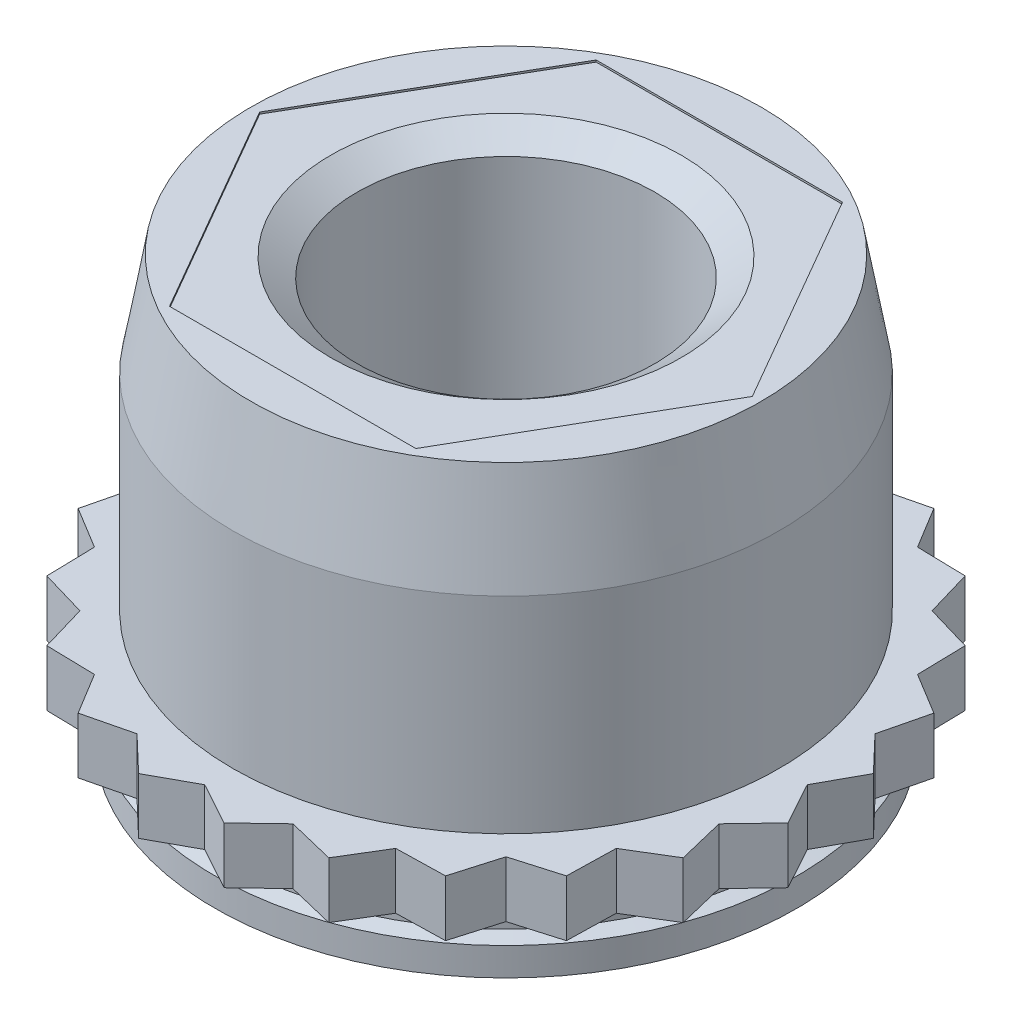
SolidWorks part; units mm, degrees
revolve "Body" add sketch "BodySke"
sketch "BodySke" plane through (0, 0, 0) normal (0, 0, 1) x (1, 0, 0)
  line L0 (3.7522, -1.0901) -> (3.7522, -0.762)
  line L1 (3.7084, 2.794) -> (3.4621, 4.191)
  line L2 (4.445, 0) -> (3.7084, 0)
  line L3 (2.0193, 4.191) -> (2.0193, -1.524)
  line L4 (2.0193, -1.524) -> (3.9497, -1.524)
  line L5 (3.9497, -1.524) -> (3.9497, -1.143)
  line L6 (3.9497, -1.143) -> (3.7522, -1.0901)
  line L7 (1.016, 0.7925) -> (3.7084, 0.7925) construction
  line L8 (3.7084, 0) -> (3.7084, 2.794)
  line L9 (0, 0) -> (0, 15.24) construction
  line L11 (3.4621, 4.191) -> (2.0193, 4.191)
  line L15 (3.7522, -0.762) -> (4.445, -0.762)
  line L16 (4.445, -0.762) -> (4.445, 0)
  dimension "Clinch_dia" = 8.89
  dimension "C_dia" = 7.8994
  dimension "Thread_min" = 4.0386
  dimension "Advance" = 0.7925
  dimension "D_dia" = 7.4168
  dimension "Height" = 4.191
  dimension "A_ht" = 1.524
  dimension "Clinching_ht" = 0.762
  dimension "Groove_dia" = 7.5044
  dimension "Chamfer_ht" = 1.397
  dimension "D1" = 10
  dimension "D2" = 75
  dimension "C_len" = 0.381
cosmetic thread "ThreadCosmetic" [suppressed]
revolve "EndChamfer" cut sketch "EndChamferSke" angle 360 about L0
sketch "EndChamferSke" plane through (0, 0, 0) normal (0, 0, 1) x (1, 0, 0)
  line L0 (0, -2.54) -> (0, 7.62) construction
  line L1 (0, 0) -> (0, 15.24) construction
  line L2 (2.413, -1.778) -> (2.413, -1.5215)
  line L3 (2.413, -1.5215) -> (2.0193, -1.2459)
  line L4 (2.0193, -1.2459) -> (2.0193, -1.778)
  line L5 (2.0193, -1.778) -> (2.413, -1.778)
  line L6 (2.413, 4.1885) -> (2.413, 4.445)
  line L7 (2.413, 4.445) -> (2.0193, 4.445)
  line L8 (2.0193, 4.445) -> (2.0193, 3.9129)
  line L9 (2.0193, 3.9129) -> (2.413, 4.1885)
  line L10 (3.4621, 4.191) -> (-3.4621, 4.191) construction
  line L11 (-3.9497, -1.524) -> (3.9497, -1.524) construction
  line L12 (2.0193, 4.191) -> (-2.0193, 4.191) construction
  dimension "Thread_nominal" = 4.826
  dimension "Thread_min" = 4.0386
  dimension "D1" = 0.254
  dimension "D2" = 34.99
  dimension "D3" = 0.254
ref_plane "Plane1" through (0, 0, 0) normal (0, 0, 1) x (1, 0, 0)
ref_plane "Plane2" through (0, 0, 0) normal (0, 1, 0) x (1, 0, 0)
ref_plane "Plane3" through (0, 0, 0) normal (1, 0, 0) x (0, 0, -1)
ref_plane "Plane4" through (0, -0.5486, 0) normal (0, 1, 0) x (-1, 0, 0)
sketch "ThdSchSke" plane through (0, 0, 0) normal (0, 0, 1) x (1, 0, 0)
  line L0 (0, -5.08) -> (0, 7.62) construction
  line L1 (0, 0) -> (0, 15.24) construction
  line L2 (0, -1.5215) -> (2.413, -1.5215) construction
  line L4 (2.413, -1.5215) -> (2.0193, -1.2458)
  line L6 (2.413, -1.5215) -> (2.0193, -1.7971)
  line L7 (2.0193, -1.2458) -> (2.0193, -1.7971)
  line L8 (2.413, -1.5215) -> (-2.413, -1.5215) construction
  dimension "Thread_nominal" = 4.826
  dimension "Thread_min" = 4.0386
revolve "ThreadSchematic" [suppressed] cut sketch "ThdSchSke" angle 360 about L0
pattern_linear "ThdSchPat" [suppressed]
sketch "CliRinCutSke" plane through (0, -0.762, 0) normal (0, -1, 0) x (1, 0, 0)
  line L0 (0.5802, 4.407) -> (0, 4.0894)
  line L1 (0, 4.0894) -> (-0.5802, 4.407)
  line L2 (0, 0) -> (0, 5.842) construction
  arc A1 (0.5802, 4.407) -> (-0.5802, 4.407) centre (0, 0) ccw
  circle A2 centre (0, 0) radius 4.0894 construction
  dimension "Angle" = 15
  dimension "Clinch_dia" = 8.89
  dimension "Clinch_minor" = 8.1788
extrude "ClinchCut" cut sketch "CliRinCutSke" against normal blind 0.762
pattern_circular "ClinchCutPat" count 24 every 15 about axis through (0, 0, 0) along (0, 1, 0) of "ClinchCut"
sketch "HexCutSke" plane through (0, 4.191, 0) normal (0, 1, 0) x (-1, 0, 0)
  line L0 (-1.6718, 2.8956) -> (1.6718, 2.8956)
  line L1 (1.6718, 2.8956) -> (3.3436, 0)
  line L2 (3.3436, 0) -> (1.6718, -2.8956)
  line L3 (1.6718, -2.8956) -> (-1.6718, -2.8956)
  line L4 (-1.6718, -2.8956) -> (-3.3436, 0)
  line L5 (-3.3436, 0) -> (-1.6718, 2.8956)
  circle A0 centre (0, 0) radius 3.3436 construction
  circle A1 centre (0, 0) radius 2.8956 construction
  dimension "Width_across_flats" = 5.7912
extrude "HexCut" cut sketch "HexCutSke" against normal blind 0.0254
equation "' \"A_ht@BodySke\" = 0.06"
equation "' \"C_dia@BodySke\" = 0.311"
equation "' \"D_dia@BodySke\" = 0.292"
equation "' \"Clinch_dia@BodySke\" = 0.35"
equation "' \"Height@BodySke\" = 0.165"
equation "' \"Advance@BodySke\" = 0.0312"
equation "' \"Thread_min@BodySke\" = 0.159"
equation "' \"Thread_nominal@ThreadCosmetic\" = 0.19"
equation "\"Width_across_flats@HexCutSke\" = \"Thread_nominal@ThreadCosmetic\" * 1.2"
equation "\"Count@ClinchCutPat\" = 24"
equation "\"Angle@ClinchCutPat\" = 360 / \"Count@ClinchCutPat\""
equation "\"Angle@CliRinCutSke\" = 360 / \"Count@ClinchCutPat\""
equation "\"Clinch_dia@CliRinCutSke\" = \"Clinch_dia@BodySke\""
equation "\"Clinch_minor@CliRinCutSke\" = \"Clinch_dia@BodySke\" * 0.92"
equation "\"C_len@BodySke\" = \"A_ht@BodySke\" * 0.25"
equation "\"Groove_dia@BodySke\" = \"C_dia@BodySke\" * 0.95"
equation "\"Clinching_ht@BodySke\" = \"A_ht@BodySke\" * 0.5"
equation "\"Depth@ClinchCut\" =  \"A_ht@BodySke\" * 0.5"
equation "\"Chamfer_ht@BodySke\" = \"Height@BodySke\" / 3"
equation "\"Thread_nominal@EndChamferSke\" = \"Thread_nominal@ThreadCosmetic\""
equation "\"Thread_min@EndChamferSke\" = \"Thread_min@BodySke\""
equation "\"D2@EndChamferSke\" = \"Vee_angle@ThdSchSke\" / 2 - 0.01"
equation "\"Thread_nominal@ThdSchSke\" = \"Thread_nominal@ThreadCosmetic\""
equation "\"Thread_min@ThdSchSke\" = \"Thread_min@BodySke\""
equation "\"Num_threads@ThdSchPat\" = int(  ( \"Height@BodySke\" + \"A_ht@BodySke\" - \"Inset@EndChamferSke\" - \"Inset_far@EndChamferSke\" ) / \"Advance@BodySke\" + 0.999 )  + 1"
equation "\"Advance@ThdSchPat\" = ( \"Height@BodySke\" + \"A_ht@BodySke\" - \"Inset@EndChamferSke\" - \"Inset_far@EndChamferSke\" ) /  (\"Num_threads@ThdSchPat\" - 1) 'relax it"
